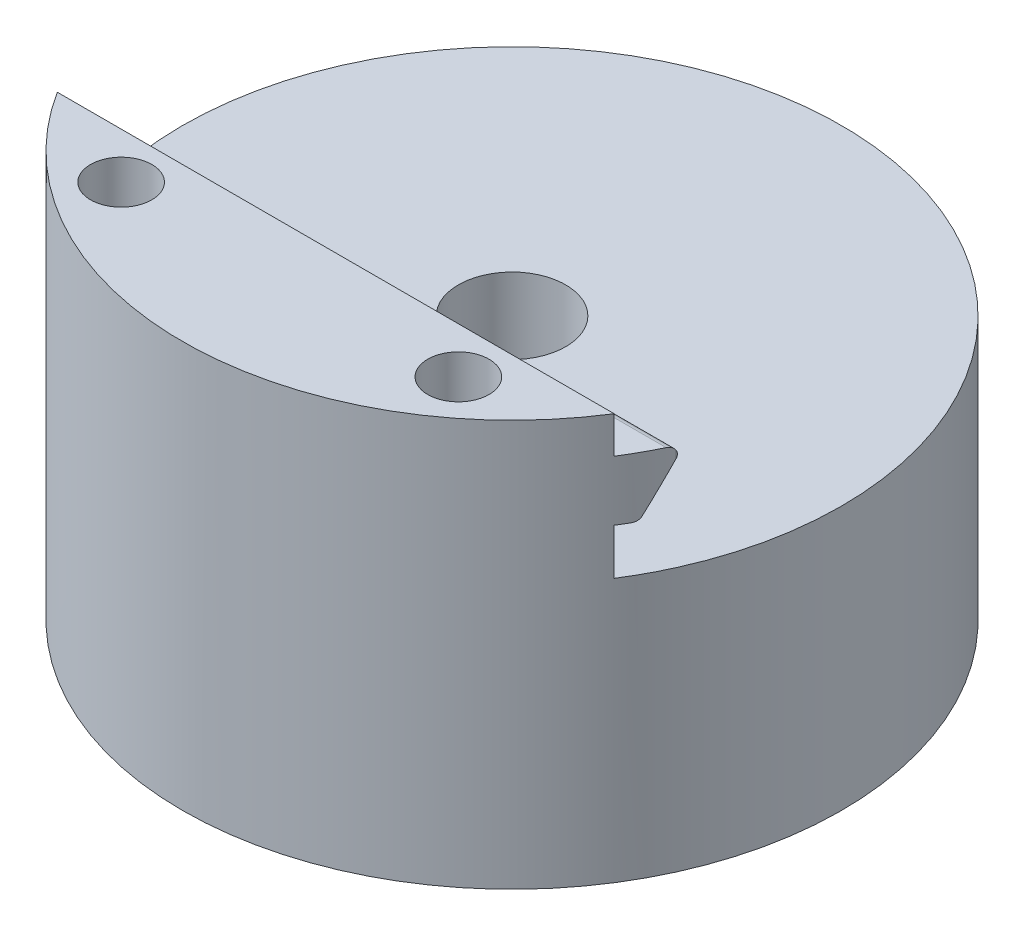
SolidWorks part; units mm, degrees
material "6061-T6 (SS)"
ref_plane "前视基准面" through (0, 0, 0) normal (0, 0, 1) x (1, 0, 0)
ref_plane "上视基准面" through (0, 0, 0) normal (0, 1, 0) x (1, 0, 0)
ref_plane "右视基准面" through (0, 0, 0) normal (1, 0, 0) x (0, 0, -1)
other "Configuration Table"
sketch "草图1" plane through (0, 0, 0) normal (0, 1, 0) x (1, 0, 0)
  circle A0 centre (0, 0) radius 21.5
  dimension "D1" = 43
extrude "凸台-拉伸1" add sketch "草图1" along normal blind 26.5
sketch "草图2" plane through (0, 26.5, 0) normal (0, 1, 0) x (1, 0, 0)
  circle A0 centre (0, 0) radius 3.5
  dimension "D1" = 7
extrude "切除-拉伸1" cut sketch "草图2" against normal blind 32
sketch "草图3" plane through (0, 0, 0) normal (1, 0, 0) x (0, 0, -1)
  line L0 (21.5, 17.2) -> (-11.5, 17.2)
  line L1 (21.5, 0) -> (21.5, 26.5) construction
  line L2 (-11.5, 17.2) -> (-11.5, 20.2)
  line L3 (-11.5, 20.2) -> (-10.5, 20.2)
  line L4 (-10.5, 20.2) -> (-8.5, 24.1)
  line L5 (-8.5, 24.1) -> (-11.5, 24.1)
  line L6 (-11.5, 24.1) -> (-11.5, 26.5)
  line L7 (21.5, 26.5) -> (-21.5, 26.5) construction
  line L8 (-11.5, 26.5) -> (21.5, 26.5)
  line L9 (21.5, 26.5) -> (21.5, 17.2)
  line L10 (-21.5, 26.5) -> (-21.5, 0) construction
  dimension "D1" = 10
  dimension "D2" = 3
  dimension "D3" = 2.4
  dimension "D4" = 3.9
  dimension "D5" = 1
  dimension "D6" = 10
  dimension "D7" = 3
extrude "切除-拉伸2" cut sketch "草图3" against normal blind 32 and the other way blind 34
fillet "圆角1" radius 0.5 2 edges at (0, 20.2, 10.5) (0, 24.1, 8.5)
sketch "草图4" plane through (0, 26.5, 0) normal (0, 1, 0) x (1, 0, 0)
  line L0 (0, -21.5) -> (0, -14.5) construction
  line L1 (0, -14.5) -> (11, -14.5) construction
  arc A0 (-18.1659, -11.5) -> (18.1659, -11.5) centre (0, 0) ccw construction
  circle A1 centre (11, -14.5) radius 2
  circle A2 centre (-11, -14.5) radius 2
  dimension "D3" = 4
  dimension "D1" = 7
  dimension "D2" = 11
extrude "切除-拉伸3" cut sketch "草图4" against normal blind 5
sketch "草图5" plane through (0, 17.2, 0) normal (0, 1, 0) x (1, 0, 0)
  line L0 (-21.5, 0) -> (21.5, 0) construction
  arc A0 (18.1659, -11.5) -> (-18.1659, -11.5) centre (0, 0) ccw construction
hole_wizard "M3 螺纹孔1" positions "3D草图1" profile "草图6" tap size "M3" standard "ISO" end condition through all
sketch3d "3D草图1"
  line L0 (-11, 21.5, 14.5) -> (-11, 26.5, 14.5) construction
  line L1 (11, 21.5, 14.5) -> (11, 26.5, 14.5) construction
  point P0 (-11, 21.5, 14.5)
  point P4 (11, 26.5, 14.5)
sketch "草图6" plane through (-11, 21.5, 14.5) normal (1, 0, 0) x (0, 0, 1)
  line L0 (0, 0) -> (0, 21.5)
  line L1 (0, 21.5) -> (1.25, 21.5)
  line L2 (1.25, 21.5) -> (1.25, 0.275)
  line L3 (1.25, 0.275) -> (1.525, 0)
  line L5 (1.525, 0) -> (0, 0)
  line L6 (-1.25, 0.275) -> (-1.525, 0) construction
  line L11 (0, -6.35) -> (0, 107.95) construction
  dimension "通孔螺纹孔钻头直径" = 2.5
  dimension "通孔螺纹孔钻头深度" = 21.5
  dimension "近端锥形沉头孔直径" = 3.05
  dimension "近端锥形沉头孔角度" = 90
cosmetic thread "孔螺蚊线1" parameters "D2"=3
cosmetic thread "孔螺蚊线2" parameters "D2"=3
